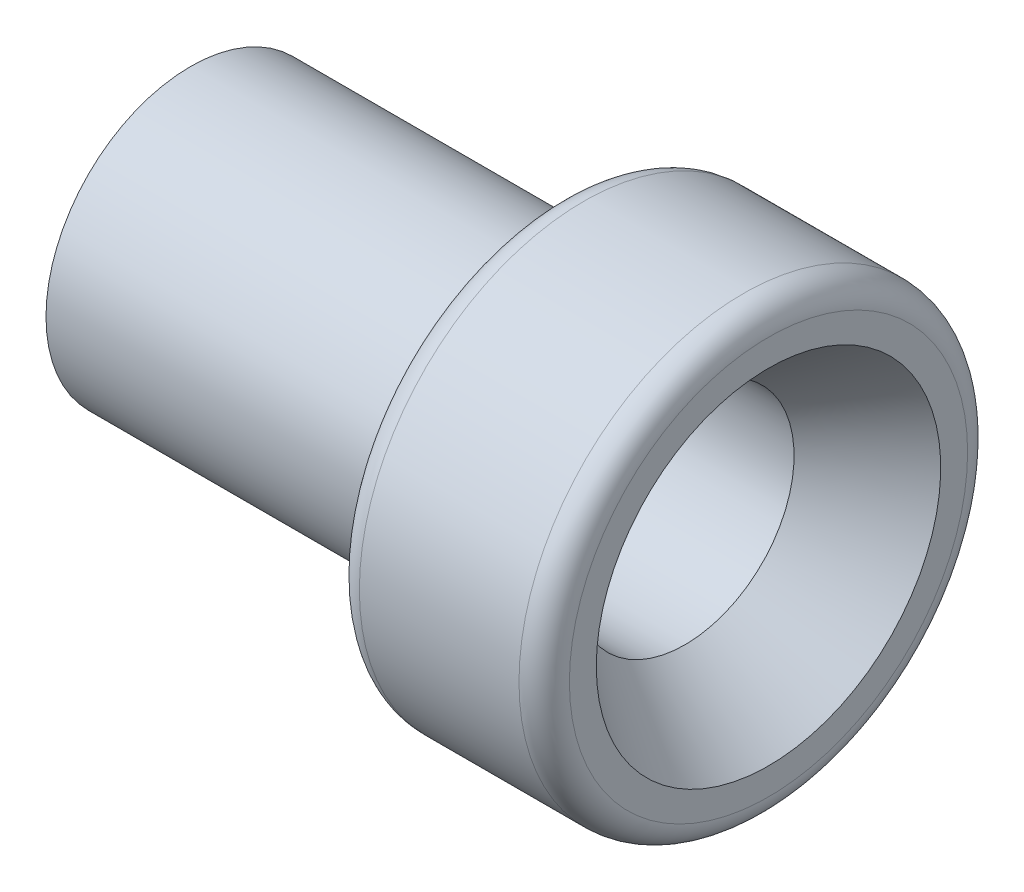
SolidWorks part; units mm, degrees
ref_plane "Front Plane" through (0, 0, 0) normal (0, 0, 1) x (1, 0, 0)
ref_plane "Top Plane" through (0, 0, 0) normal (0, 1, 0) x (1, 0, 0)
ref_plane "Right Plane" through (0, 0, 0) normal (1, 0, 0) x (0, 0, -1)
sketch "Sketch1" plane through (0, 0, 0) normal (0, 0, 1) x (1, 0, 0)
  line L0 (-4.3688, 0) -> (4.3688, 0) construction
  line L1 (-4.3688, 1.651) -> (3.1048, 1.651)
  line L2 (3.1048, 1.651) -> (4.3688, 2.6035)
  line L4 (4.3688, 2.6035) -> (4.3688, 3.0099)
  line L5 (3.9878, 3.3909) -> (1.5748, 3.3909)
  line L6 (1.1938, 3.0099) -> (1.1938, 2.1844)
  line L7 (1.1938, 2.1844) -> (-4.3688, 2.1844)
  line L8 (-4.3688, 1.651) -> (-4.3688, 2.1844)
  arc A0 (4.3688, 3.0099) -> (3.9878, 3.3909) centre (3.9878, 3.0099) ccw
  arc A1 (1.5748, 3.3909) -> (1.1938, 3.0099) centre (1.5748, 3.0099) ccw
  point P12 (4.3688, 3.3909)
  point P15 (1.1938, 3.3909)
  dimension "D2" = 0.381
  dimension "D1" = 37
  dimension "M" = 8.7376
  dimension "G" = 6.7818
  dimension "J" = 3.175
  dimension "B" = 3.302
  dimension "C" = 4.3688
  dimension "F" = 5.207
revolve "Revolve1" add sketch "Sketch1" angle 360 about L0
